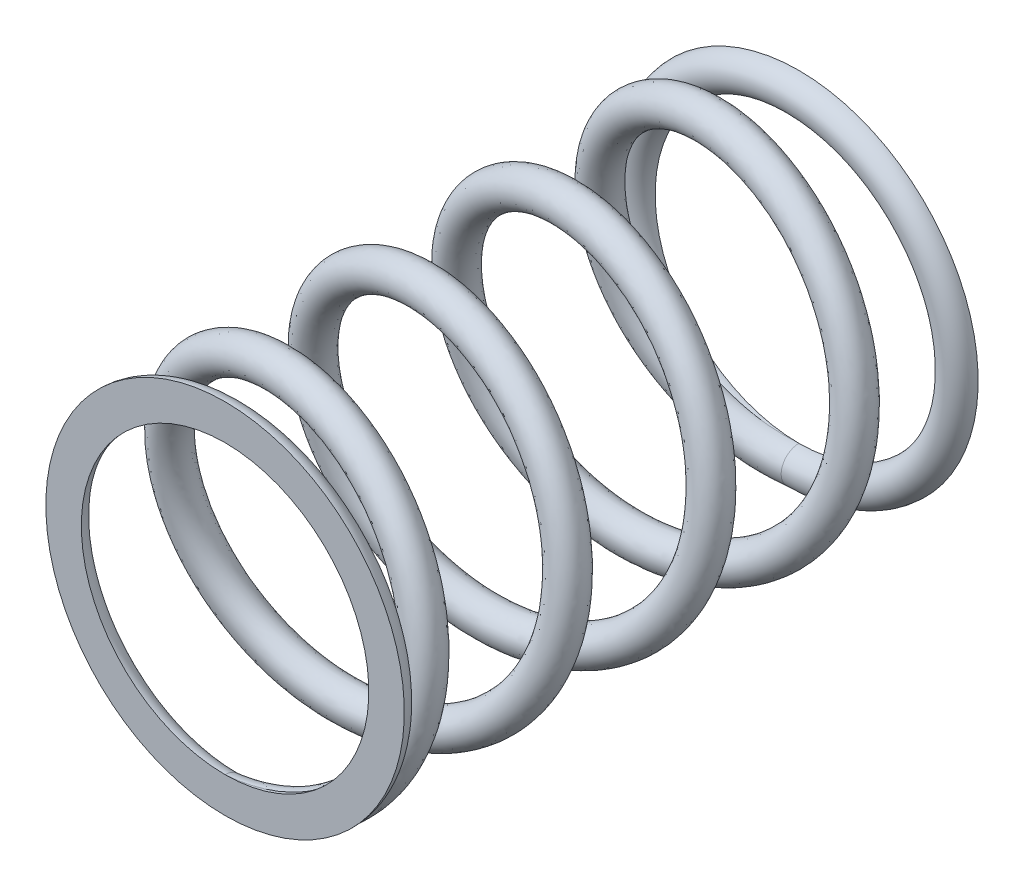
SolidWorks part; units mm, degrees
ref_plane "Piano frontale" through (0, 0, 0) normal (0, 0, 1) x (1, 0, 0)
ref_plane "Piano superiore" through (0, 0, 0) normal (0, 1, 0) x (1, 0, 0)
ref_plane "Piano destro" through (0, 0, 0) normal (1, 0, 0) x (0, 0, -1)
sketch "Schizzo1" plane through (0, 0, 0) normal (0, 0, 1) x (1, 0, 0)
  circle A0 centre (0, 0) radius 4.55
  dimension "D1" = 9.1
curve "Elica/Spirale1" pitch 4.0421 height 16.1684 turns 4
sketch "Schizzo19" plane through (0, 0, 0) normal (1, 0, 0) x (0, 0, -1)
  line L0 (0, -4.55) -> (0, 0) construction
  circle A0 centre (0, -4.55) radius 0.5
  spline S0 degree 3 poles (0, -4.55) (-0.0837, -4.55) (-0.2529, -4.3131) (-0.5052, -3.3011) (-0.7579, -1.7865) (-1.0105, 0) (-1.2632, 1.7865) (-1.5158, 3.3011) (-1.7684, 4.3131) (-2.0211, 4.6685) (-2.2737, 4.3131) (-2.5263, 3.3011) (-2.8632, 1.2817) (-3.2, -1.2817) (-3.5368, -3.3011) (-3.7895, -4.3131) (-4.0421, -4.6685) (-4.2947, -4.3131) (-4.5474, -3.3011) (-4.8842, -1.2817) (-5.221, 1.2817) (-5.5579, 3.3011) (-5.8105, 4.3131) (-6.0632, 4.6685) (-6.3158, 4.3131) (-6.5684, 3.3011) (-6.9053, 1.2817) (-7.2421, -1.2817) (-7.5789, -3.3011) (-7.8316, -4.3131) (-8.0842, -4.6685) (-8.3368, -4.3131) (-8.5895, -3.3011) (-8.9263, -1.2817) (-9.2632, 1.2817) (-9.6, 3.3011) (-9.8526, 4.3131) (-10.1053, 4.6685) (-10.3579, 4.3131) (-10.6105, 3.3011) (-10.9474, 1.2817) (-11.2842, -1.2817) (-11.621, -3.3011) (-11.8737, -4.3131) (-12.1263, -4.6685) (-12.3789, -4.3131) (-12.6316, -3.3011) (-12.9684, -1.2817) (-13.3053, 1.2817) (-13.6421, 3.3011) (-13.8947, 4.3131) (-14.1474, 4.6685) (-14.4, 4.3131) (-14.6526, 3.3011) (-14.9053, 1.7865) (-15.1579, 0) (-15.4105, -1.7865) (-15.6632, -3.3011) (-15.9155, -4.3131) (-16.0847, -4.55) (-16.1684, -4.55) knots 0 0 0 0 0.015625 0.03125 0.046875 0.0625 0.078125 0.09375 0.109375 0.125 0.140625 0.15625 0.171875 0.203125 0.21875 0.234375 0.25 0.265625 0.28125 0.296875 0.328125 0.34375 0.359375 0.375 0.390625 0.40625 0.421875 0.453125 0.46875 0.484375 0.5 0.515625 0.53125 0.546875 0.578125 0.59375 0.609375 0.625 0.640625 0.65625 0.671875 0.703125 0.71875 0.734375 0.75 0.765625 0.78125 0.796875 0.828125 0.84375 0.859375 0.875 0.890625 0.90625 0.921875 0.9375 0.953125 0.96875 0.984375 1 1 1 1 construction
  dimension "D1" = 1
sweep "Sweep1" add profiles "Schizzo19" path "Elica/Spirale1"
sketch "Schizzo8" plane through (0, 0, 0) normal (0, 1, 0) x (1, 0, 0)
  line L0 (0, 0) -> (0, -17.2452) construction
sketch "Schizzo17" plane through (0, 0, 0) normal (-1, 0, 0) x (0, 0, 1)
  line L0 (-1000, 0) -> (49000, 0) construction
  circle A1 centre (16.1684, -4.55) radius 0.5
  circle A2 centre (16.1684, -4.55) radius 0.5
  dimension "D1" = 0
revolve "Rivoluzione3" add sketch "Schizzo17" angle 360 about L0
sketch "Schizzo18" plane through (0, 0, 0) normal (1, 0, 0) x (0, 0, -1)
  line L0 (-1000, 0) -> (49000, 0) construction
  circle A1 centre (0, -4.55) radius 0.5
  circle A2 centre (0, -4.55) radius 0.5
  dimension "D1" = 0
revolve "Rivoluzione4" add sketch "Schizzo18" angle 360 about L0
sketch "Schizzo23" plane through (0, 0, 0) normal (0, 1, 0) x (1, 0, 0)
  line L0 (4.55, 0.5) -> (-4.55, 0.5) construction
  line L1 (-5.05, 0) -> (5.05, 0)
  line L2 (-5.05, 0) -> (-5.05, 0.5)
  line L3 (-5.05, 0.5) -> (5.05, 0.5)
  line L4 (5.05, 0) -> (5.05, 0.5)
  line L5 (-5.05, 0) -> (5.05, 0.5) construction
  line L6 (-5.05, 0.5) -> (5.05, 0) construction
  line L7 (-4.55, -16.6684) -> (4.55, -16.6684) construction
  line L8 (5.05, -16.1684) -> (-5.05, -16.1684)
  line L9 (5.05, -16.1684) -> (5.05, -16.6684)
  line L10 (5.05, -16.6684) -> (-5.05, -16.6684)
  line L11 (-5.05, -16.1684) -> (-5.05, -16.6684)
  line L12 (5.05, -16.1684) -> (-5.05, -16.6684) construction
  line L13 (5.05, -16.6684) -> (-5.05, -16.1684) construction
  arc A0 (-4.55, 0.5) -> (-4.55, -0.5) centre (-4.55, 0) ccw construction
  arc A1 (4.55, -0.5) -> (4.55, 0.5) centre (4.55, 0) ccw construction
  arc A2 (4.55, -16.6684) -> (4.55, -15.6684) centre (4.55, -16.1684) ccw construction
  arc A3 (-4.55, -15.6684) -> (-4.55, -16.6684) centre (-4.55, -16.1684) ccw construction
  point P4 (0, 0.25)
  point P19 (0, -16.4184)
  point P23 (-5.05, -16)
extrude "Taglio-Estrusione1" cut sketch "Schizzo23" against normal through all both and the other way through all
